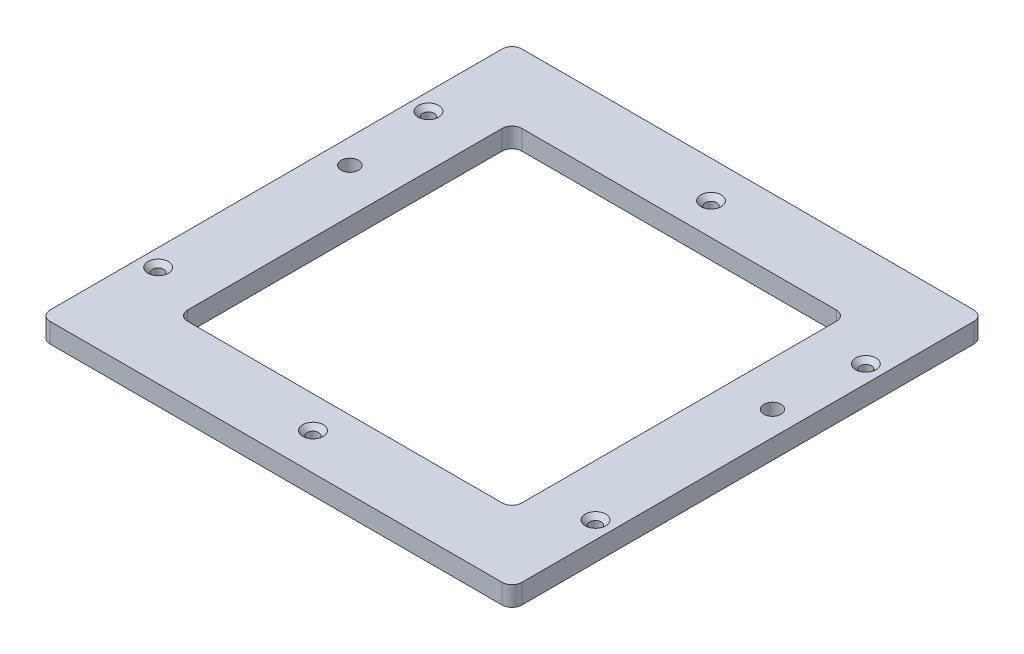
SolidWorks part; units mm, degrees
material "Plain Carbon Steel"
ref_plane "Front Plane" through (0, 0, 0) normal (0, 0, 1) x (1, 0, 0)
ref_plane "Top Plane" through (0, 0, 0) normal (0, 1, 0) x (1, 0, 0)
ref_plane "Right Plane" through (0, 0, 0) normal (1, 0, 0) x (0, 0, -1)
sketch "Sketch1" plane through (0, 0, 0) normal (0, 1, 0) x (1, 0, 0)
  line L1 (-120, 120) -> (120, 120)
  line L2 (-120, 120) -> (-120, -120)
  line L3 (-120, -120) -> (120, -120)
  line L4 (120, 120) -> (120, -120)
  line L5 (-120, 120) -> (120, -120) construction
  line L6 (-120, -120) -> (120, 120) construction
  point P0 (0, 0)
  dimension "D1" = 240
  dimension "D2" = 240
extrude "Boss-Extrude1" add sketch "Sketch1" along normal blind 10
sketch "Sketch2" plane through (0, 10, 0) normal (0, 1, 0) x (1, 0, 0)
  line L0 (-118.75, -118.75) -> (118.75, -118.75) construction
  line L1 (-120, 120) -> (-120, -120) construction
  line L2 (120, 118.75) -> (-120, 118.75)
  line L3 (118.75, 118.75) -> (-118.75, 118.75) construction
  line L4 (120, -120) -> (120, 120) construction
  line L5 (-120, -120) -> (120, -120) construction
  point P0 (0, 101.25)
  point P1 (111.25, 68.75)
  point P2 (111.25, -68.75)
  point P5 (-111.25, 68.75)
  point P6 (-111.25, -68.75)
  point P7 (0, -101.25)
  dimension "D2" = 1.25
  dimension "D3" = 1.25
  dimension "D4" = 1.25
  dimension "D5" = 1.25
  dimension "D6" = 1.25
  dimension "D7" = 17.5
  dimension "D8" = 17.5
  dimension "D9" = 50
  dimension "D10" = 50
  dimension "D11" = 7.5
  dimension "D12" = 7.5
  dimension "D1" = 1.25
hole_wizard "CSK for M5 Flat Head Machine Screw1" positions "Sketch3" profile "Sketch4" countersink size "M5" standard "ANSI Metric" end condition through all
sketch "Sketch3" plane through (0, 10, 0) normal (0, 1, 0) x (1, 0, 0)
  point P0 (-111.25, 68.75)
  point P3 (0, 101.25)
  point P6 (111.25, 68.75)
  point P9 (111.25, -68.75)
  point P12 (0, -101.25)
  point P15 (-111.25, -68.75)
sketch "Sketch4" plane through (-111.25, 10, -68.75) normal (1, 0, 0) x (0, 0, 1)
  line L0 (0, 0) -> (0, 10)
  line L1 (0, 10) -> (2.9, 10)
  line L2 (2.9, 10) -> (2.9, 2.3)
  line L3 (2.9, 2.3) -> (5.2, 0)
  line L5 (5.2, 0) -> (0, 0)
  line L6 (-2.9, 2.3) -> (-5.2, 0) construction
  line L11 (0, -6.35) -> (0, 107.95) construction
  dimension "Thru Hole Dia." = 5.8
  dimension "Thru Hole Depth" = 10
  dimension "Near C'Sink Dia." = 10.4
  dimension "Near C'Sink Angle" = 90
fillet "Fillet1" radius 5 4 edges at (-120, 5, 120) (-120, 5, -120) (120, 5, -120) (120, 5, 120)
sketch "Sketch5" plane through (0, 10, 0) normal (0, 1, 0) x (1, 0, 0)
  circle A0 centre (107.5, 25) radius 5
  circle A1 centre (-107.5, 25) radius 5
  dimension "D1" = 10
  dimension "D2" = 10
  dimension "D3" = 25
  dimension "D4" = 107.5
  dimension "D5" = 107.5
hole_wizard "Tap Drill for M10x1.25 Tap1" positions "Sketch6" profile "Sketch7" hole size "M10x1.25" standard "ANSI Metric"
sketch "Sketch6" plane through (0, 10, 0) normal (0, 1, 0) x (1, 0, 0)
  point P0 (107.5, 25)
  point P3 (-107.5, 25)
sketch "Sketch7" plane through (107.5, 10, -25) normal (1, 0, 0) x (0, 0, 1)
  line L0 (0, 0) -> (0, 22.3938)
  line L1 (0, 22.3938) -> (4.4, 19.75)
  line L2 (4.4, 19.75) -> (4.4, 0)
  line L5 (4.4, 0) -> (0, 0)
  line L10 (0, 22.3938) -> (-4.4, 19.75) construction
  line L11 (0, -6.35) -> (0, 107.95) construction
  dimension "Hole Dia." = 8.8
  dimension "Hole Depth" = 19.75
  dimension "Drill Angle" = 118
sketch "Sketch8" plane through (0, 10, 0) normal (0, 1, 0) x (1, 0, 0)
  line L8 (-85, 85) -> (-85, -85)
  line L9 (-85, -85) -> (85, -85)
  line L10 (85, -85) -> (85, 85)
  line L11 (85, 85) -> (-85, 85)
  line L12 (-85, 85) -> (-85, -85)
  line L13 (-85, -85) -> (85, -85)
  line L14 (85, -85) -> (85, 85)
  line L15 (85, 85) -> (-85, 85)
  dimension "D1" = 35
extrude "Cut-Extrude1" cut sketch "Sketch8" against normal blind 10
fillet "Fillet2" radius 5 4 edges at (85, 5, 85) (-85, 5, 85) (85, 5, -85) (-85, 5, -85)
